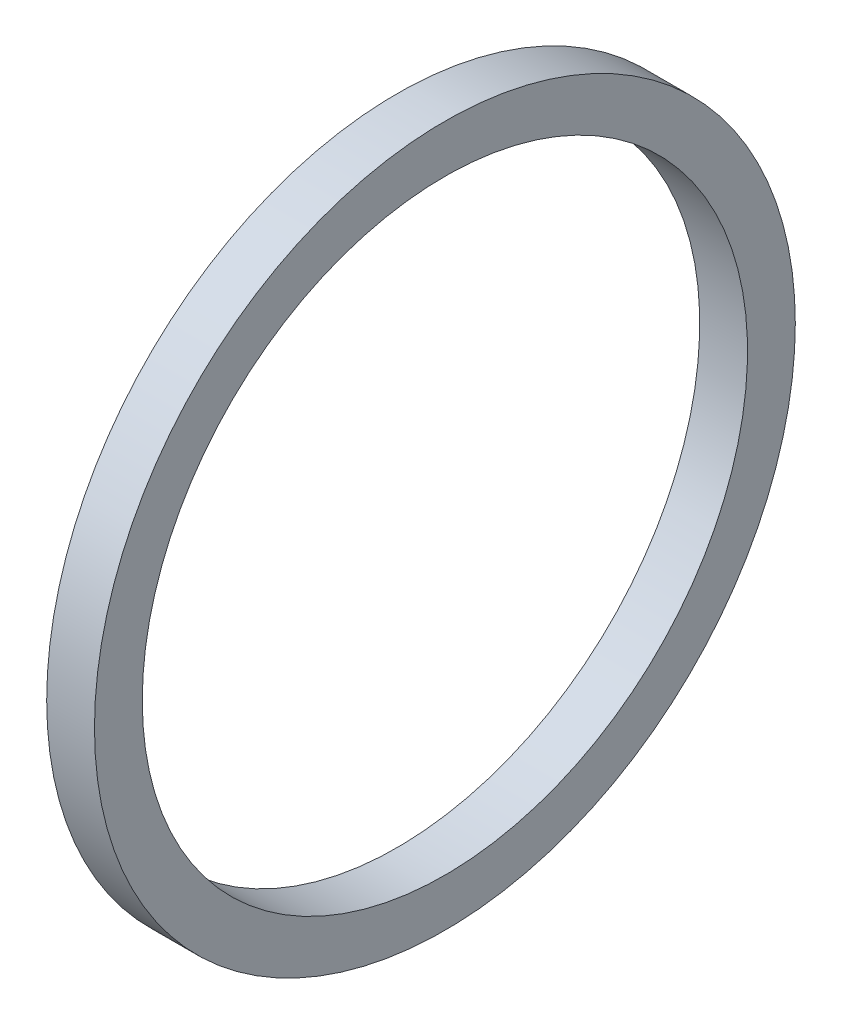
SolidWorks part; units mm, degrees
ref_plane "Front Plane" through (0, 0, 0) normal (0, 0, 1) x (1, 0, 0)
ref_plane "Top Plane" through (0, 0, 0) normal (0, 1, 0) x (1, 0, 0)
ref_plane "Right Plane" through (0, 0, 0) normal (1, 0, 0) x (0, 0, -1)
sketch "Sketch1" plane through (0, 0, 0) normal (0, 1, 0) x (1, 0, 0)
  line L0 (0, 0) -> (2.114, 0) construction
  line L1 (1.5, 19) -> (-1.5, 19)
  line L2 (1.5, 19) -> (1.5, 22)
  line L3 (1.5, 22) -> (-1.5, 22)
  line L4 (-1.5, 19) -> (-1.5, 22)
  line L5 (1.5, 19) -> (-1.5, 22) construction
  line L6 (1.5, 22) -> (-1.5, 19) construction
  point P0 (0, 20.5)
  dimension "D1" = 3
  dimension "D2" = 19
  dimension "D3" = 3
revolve "Revolve1" add sketch "Sketch1" angle 360 about L0
